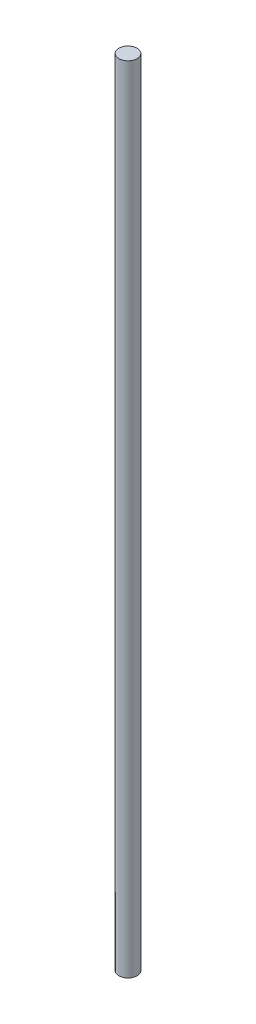
SolidWorks part; units mm, degrees
ref_plane "Front Plane" through (0, 0, 0) normal (0, 0, 1) x (1, 0, 0)
ref_plane "Top Plane" through (0, 0, 0) normal (0, 1, 0) x (1, 0, 0)
ref_plane "Right Plane" through (0, 0, 0) normal (1, 0, 0) x (0, 0, -1)
sketch "Sketch1" plane through (0, 0, 0) normal (0, 1, 0) x (1, 0, 0)
  circle A0 centre (0, 0) radius 4
  dimension "D1" = 8
extrude "Boss-Extrude1" add sketch "Sketch1" along normal blind 350
equation "\"Y-ROD-SPACING\"=75"
equation "\"Y-BED-OFFSET\"=2"
equation "\"Y-BED-ROD-INSET\"=3.5"
equation "\"T-SLOT-NUT-FILLET-RADIUS\"=0.25"
equation "\"T-SLOT-SCREW-SHAFT-RADIUS\"=1.75"
equation "\"T-SLOT-SCREW-SHAFT-CUTOUT-LENGTH\"=10.5"
equation "\"T-SLOT-NUT-DEPTH\"=4.2"
equation "\"T-SLOT-NUT-WIDTH\"=3"
equation "\"T-SLOT-NUT-END-DISTANCE\"=8"
equation "\"ACRYLIC-THICKNESS\"=10"
equation "\"ACRYLIC-TAB-CUTOUT-SIZE\"=\"ACRYLIC-THICKNESS\"+\"ACRYLIC-TAB-TOLERANCE\"*2"
equation "\"ACRYLIC-TAB-WIDTH\"=\"ACRYLIC-THICKNESS\""
equation "\"ACRYLIC-M3-HOLE\"=3.2"
equation "\"SMOOTHROD-CAP-SCREW-DISTANCE\"=20"
equation "\"FRAME-WIDTH-INNER\"=370"
equation "\"NEMA17-HOLE-SPACING\"=31"
equation "\"NEMA17-CENTRAL-CUTOUT\"=22.5"
equation "\"Z-BRACKET-REACH\"=55"
equation "\"TOP-BRACKET-SPACING\"=40"
equation "\"SMOOTHROD-X-LENGTH\"=350"
equation "\"SMOOTHROD-Y-LENGTH\"=350"
equation "\"SMOOTHROD-Z-LENGTH\"=350"
equation "\"SMOOTHROD-TIGHTENING-HEADROOM\"=1"
equation "\"LEADSCREW-Z-LENGTH\"=300"
equation "\"D1@Boss-Extrude1\"=\"SMOOTHROD-Y-LENGTH\""
